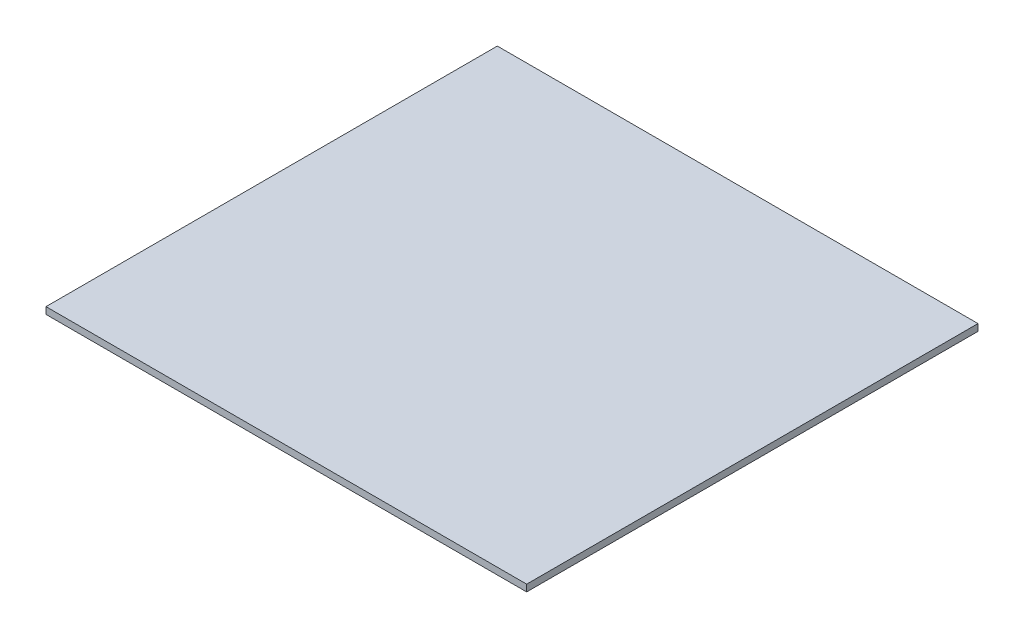
SolidWorks part; units mm, degrees
ref_plane "Front Plane" through (0, 0, 0) normal (0, 0, 1) x (1, 0, 0)
ref_plane "Top Plane" through (0, 0, 0) normal (0, 1, 0) x (1, 0, 0)
ref_plane "Right Plane" through (0, 0, 0) normal (1, 0, 0) x (0, 0, -1)
sketch "Sketch1" plane through (0, 0, 0) normal (0, 1, 0) x (1, 0, 0)
  line L1 (0, 0) -> (213, 0)
  line L2 (0, 0) -> (0, 200)
  line L3 (0, 200) -> (213, 200)
  line L4 (213, 0) -> (213, 200)
  dimension "D1" = 200
  dimension "D2" = 213
extrude "Boss-Extrude1" add sketch "Sketch1" along normal blind 3
